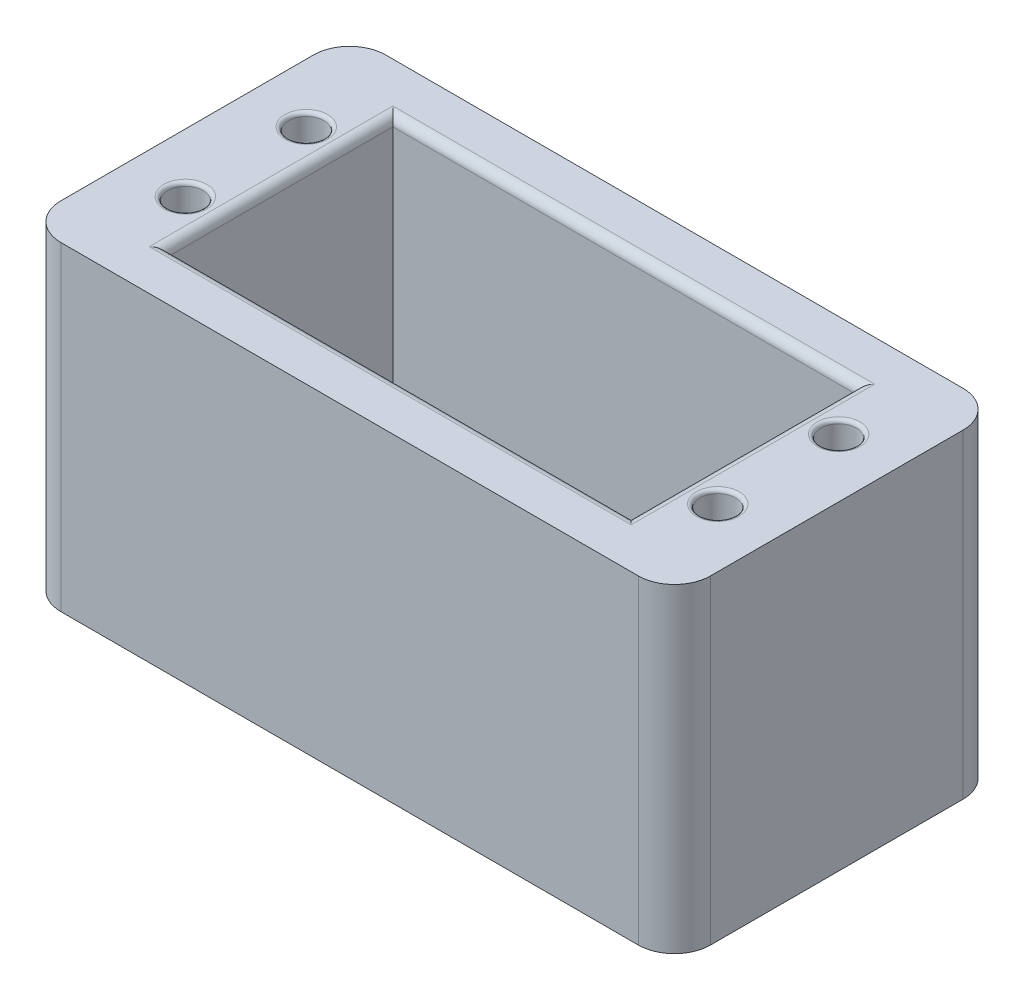
SolidWorks part; units mm, degrees
ref_plane "Front Plane" through (0, 0, 0) normal (0, 0, 1) x (1, 0, 0)
ref_plane "Top Plane" through (0, 0, 0) normal (0, 1, 0) x (1, 0, 0)
ref_plane "Right Plane" through (0, 0, 0) normal (1, 0, 0) x (0, 0, -1)
sketch "Sketch1" plane through (0, 0, 0) normal (0, 1, 0) x (1, 0, 0)
  line L1 (-45.72, 22.86) -> (45.72, 22.86)
  line L2 (-45.72, 22.86) -> (-45.72, -22.86)
  line L3 (-45.72, -22.86) -> (45.72, -22.86)
  line L4 (45.72, 22.86) -> (45.72, -22.86)
  line L5 (-45.72, 22.86) -> (45.72, -22.86) construction
  line L6 (-45.72, -22.86) -> (45.72, 22.86) construction
  point P0 (0, 0)
  point P6 (0, 0)
  point P9 (0, 0)
  point P10 (0, 0)
  point P11 (-45.3012, 0)
  dimension "D3" = 91.44
  dimension "D4" = 45.72
extrude "Boss-Extrude1" add sketch "Sketch1" along normal blind 45
sketch "Sketch2" plane through (0, 45, 0) normal (0, 1, 0) x (1, 0, 0)
  line L1 (-32.639, 15.875) -> (32.639, 15.875)
  line L2 (-32.639, 15.875) -> (-32.639, -15.875)
  line L3 (-32.639, -15.875) -> (32.639, -15.875)
  line L4 (32.639, 15.875) -> (32.639, -15.875)
  line L5 (-32.639, 15.875) -> (32.639, -15.875) construction
  line L6 (-32.639, -15.875) -> (32.639, 15.875) construction
  point P0 (0, 0)
  dimension "D1" = 65.278
  dimension "D2" = 31.75
extrude "Cut-Extrude1" cut sketch "Sketch2" against normal blind 40
sketch "Sketch3" plane through (0, 45, 0) normal (0, 1, 0) x (1, 0, 0)
  line L0 (0, 31.3041) -> (0, -31.3041) construction
  circle A0 centre (37.465, 8.509) radius 2.5
  circle A1 centre (37.465, -8.509) radius 2.5
  circle A2 centre (-37.465, -8.509) radius 2.5
  circle A3 centre (-37.465, 8.509) radius 2.5
  point P12 (0, 0)
  point P13 (0, 0)
  dimension "D1" = 5
  dimension "D2" = 17.018
  dimension "D3" = 8.509
  dimension "D4" = 37.465
extrude "Cut-Extrude2" cut sketch "Sketch3" against normal blind 25.4
fillet "Fillet1" radius 5.08 4 edges at (-45.72, 22.5, 22.86) (-45.72, 22.5, -22.86) (45.72, 22.5, 22.86) (45.72, 22.5, -22.86)
fillet "Fillet3" radius 1.27 4 edges at (-32.639, 45, 0) (0, 45, 15.875) (32.639, 45, 0) (0, 45, -15.875)
fillet "Fillet4" radius 0.508 4 edges at (-37.465, 45, 6.009) (-37.465, 45, -11.009) (37.465, 45, 11.009) (37.465, 45, -6.009)
